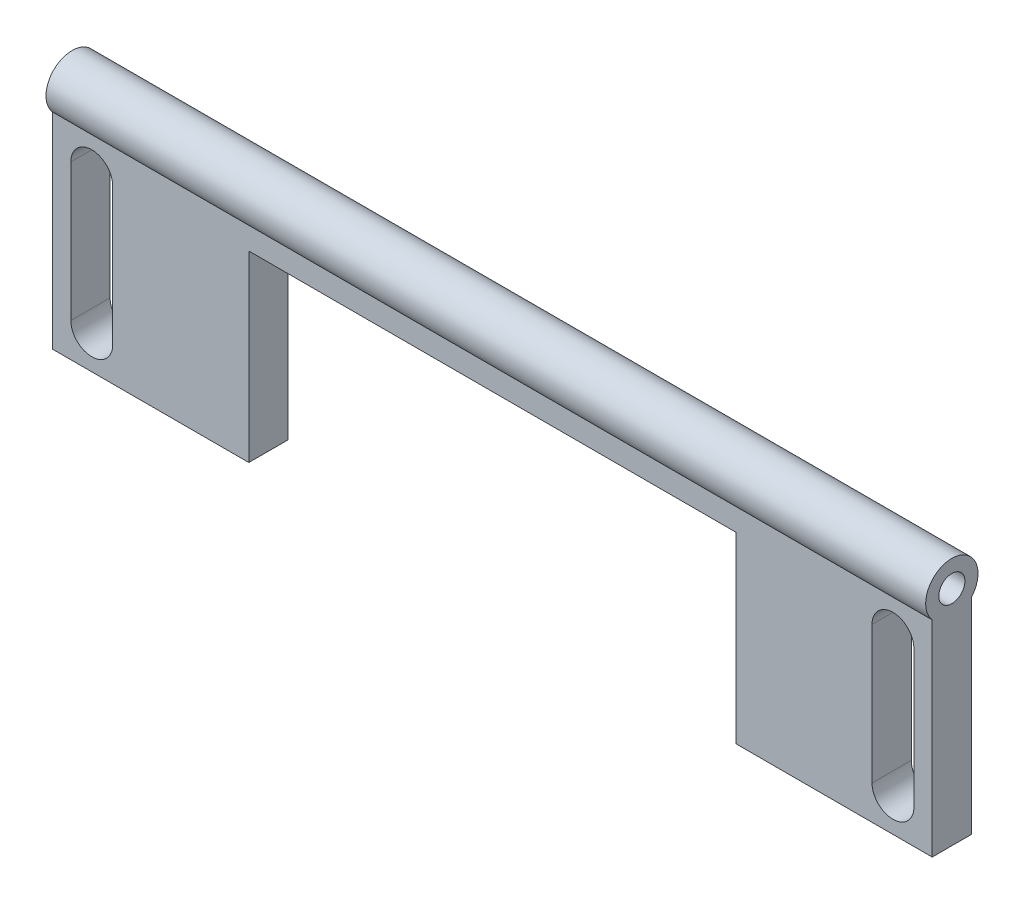
SolidWorks part; units mm, degrees
ref_plane "Front Plane" through (0, 0, 0) normal (0, 0, 1) x (1, 0, 0)
ref_plane "Top Plane" through (0, 0, 0) normal (0, 1, 0) x (1, 0, 0)
ref_plane "Right Plane" through (0, 0, 0) normal (1, 0, 0) x (0, 0, -1)
sketch "Sketch1" plane through (0, 0, 0) normal (1, 0, 0) x (0, 0, -1)
  line L0 (0, 15.7) -> (0, 0)
  line L1 (0, 0) -> (3, 0)
  line L2 (3, 0) -> (3, 15.7)
  circle A0 centre (1.5, 17.0229) radius 1
  arc A1 (0, 15.7) -> (3, 15.7) centre (1.5, 17.0229) cw
  dimension "D3" = 2
  dimension "D1" = 3
  dimension "D2" = 15.7
  dimension "D4" = 2
  dimension "D5" = 1.5
extrude "Boss-Extrude1" add sketch "Sketch1" along normal blind 33.615 contours A1 L0 L1 L2 A0
sketch "Sketch2" plane through (0, 0, -3) normal (0, 0, -1) x (-1, 0, 0)
  line L0 (-3, 13.1) -> (-3, 2.6) construction
  line L1 (-1.4, 13.1) -> (-1.4, 2.6)
  line L2 (-4.6, 13.1) -> (-4.6, 2.6)
  line L3 (0, 0) -> (0, 15.7) construction
  line L4 (-33.615, 0) -> (0, 0) construction
  arc A0 (-1.4, 13.1) -> (-4.6, 13.1) centre (-3, 13.1) ccw
  arc A1 (-4.6, 2.6) -> (-1.4, 2.6) centre (-3, 2.6) ccw
  point P2 (-3, 7.85)
  dimension "D1" = 1.6
  dimension "D2" = 10.5
  dimension "D3" = 3
  dimension "D4" = 7.85
extrude "Cut-Extrude1" cut sketch "Sketch2" against normal through all
mirror "Mirror1" about plane through (33.615, 0, 0) normal (1, 0, 0) of "Cut-Extrude1", "Boss-Extrude1"
sketch "Sketch3" plane through (0, 0, -3) normal (0, 0, -1) x (-1, 0, 0)
  line L0 (-52.23, 14) -> (-52.23, 0)
  line L1 (-52.23, 14) -> (-15, 14)
  line L2 (-15, 0) -> (-52.23, 0)
  line L3 (-15, 14) -> (-15, 0)
  line L4 (0, 0) -> (0, 15.7) construction
  line L5 (-67.23, 0) -> (0, 0) construction
  line L6 (-62.63, 13.1) -> (-62.63, 2.6) construction
  dimension "D1" = 10.4
  dimension "D4" = 15
extrude "Cut-Extrude3" cut sketch "Sketch3" against normal blind 10
